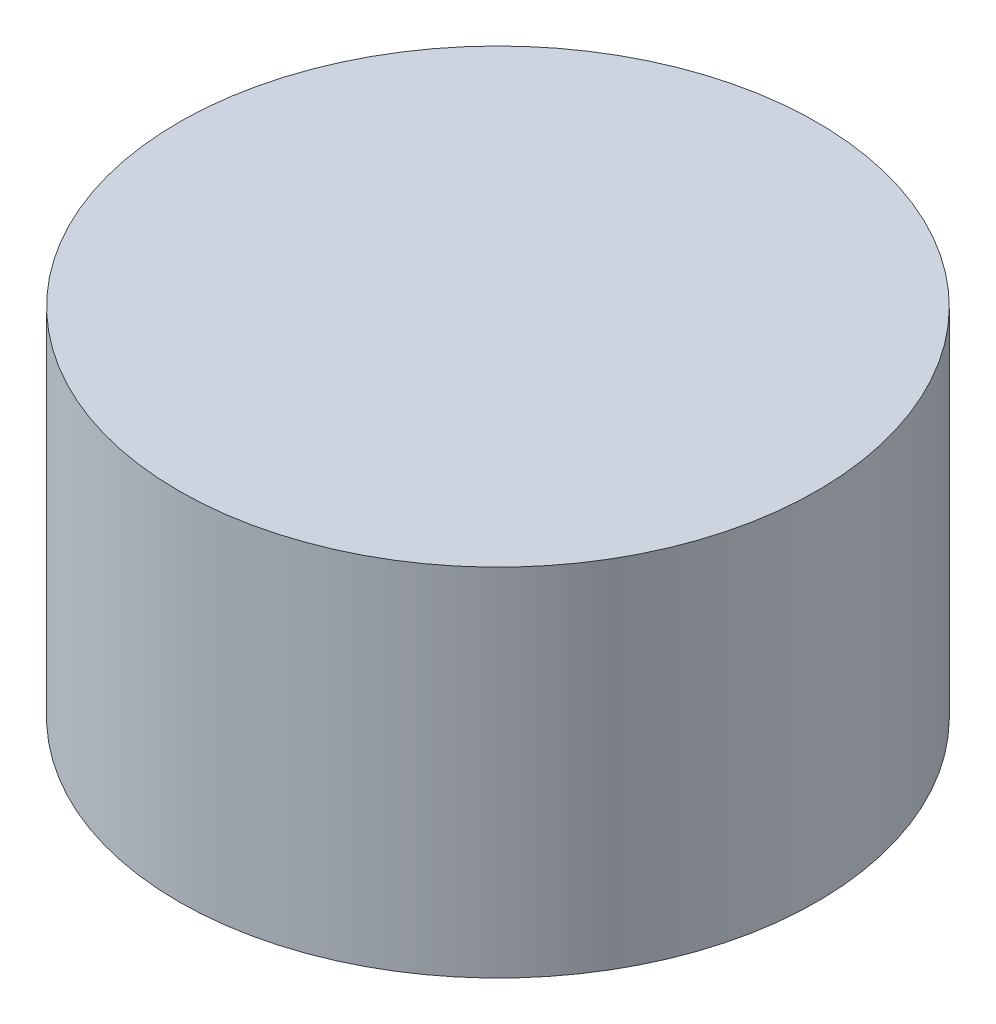
SolidWorks part; units mm, degrees
ref_plane "Piano frontale" through (0, 0, 0) normal (0, 0, 1) x (1, 0, 0)
ref_plane "Piano superiore" through (0, 0, 0) normal (0, 1, 0) x (1, 0, 0)
ref_plane "Piano destro" through (0, 0, 0) normal (1, 0, 0) x (0, 0, -1)
sketch "Schizzo1" plane through (0, 0, 0) normal (0, 1, 0) x (1, 0, 0)
  circle A0 centre (0, 0) radius 14.5
  dimension "D1" = 29
extrude "Estrusione-Estrusione1" add sketch "Schizzo1" along normal blind 16.1672
